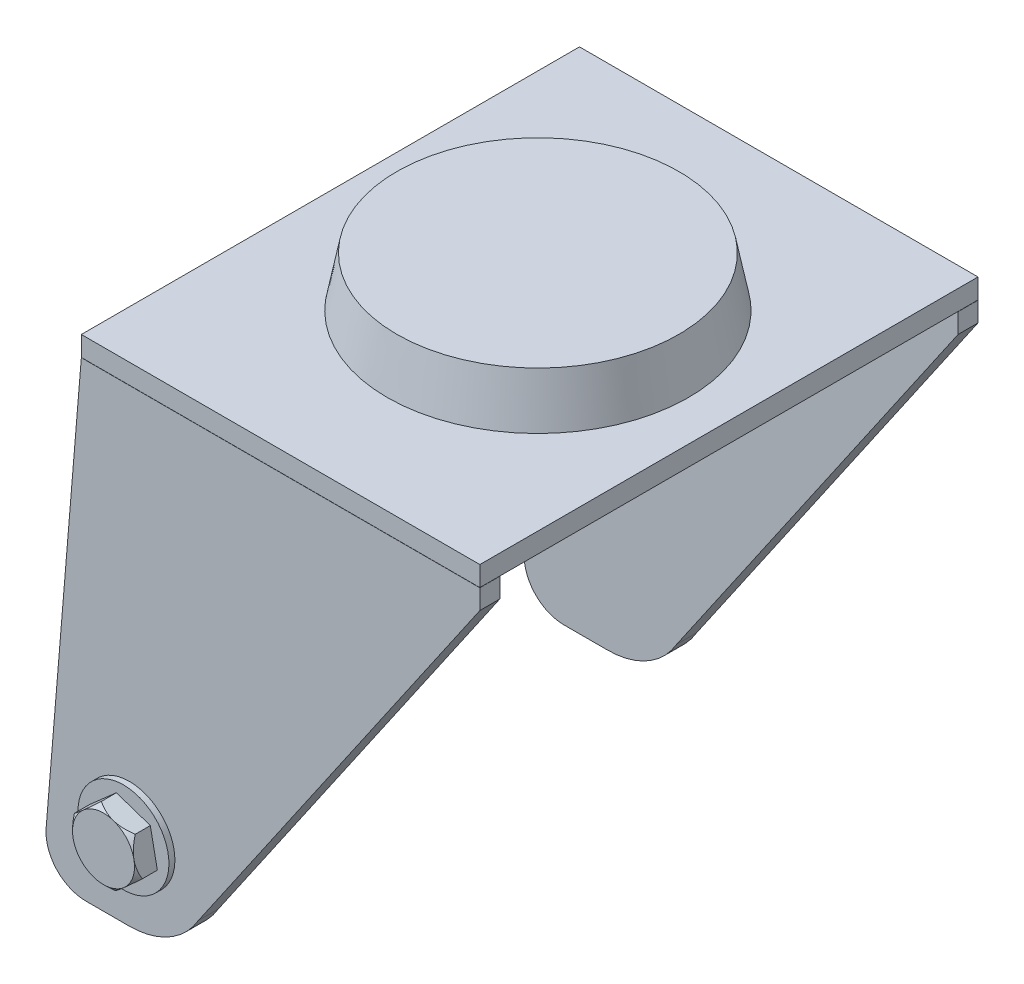
SolidWorks part; units mm, degrees
ref_plane "Front Plane" through (0, 0, 0) normal (0, 0, 1) x (1, 0, 0)
ref_plane "Top Plane" through (0, 0, 0) normal (0, 1, 0) x (1, 0, 0)
ref_plane "Right Plane" through (0, 0, 0) normal (1, 0, 0) x (0, 0, -1)
sketch "Sketch1" plane through (0, 0, 0) normal (0, 0, 1) x (1, 0, 0)
  line L0 (-24.1267, 195) -> (-41.8107, -18.4906)
  line L2 (0, -40.1416) -> (-21.879, -40.1416)
  line L4 (175.8733, 185) -> (175.8733, 195)
  line L6 (175.8733, 195) -> (-24.1267, 195)
  line L7 (107.781, 195) -> (175.8733, 195)
  line L9 (175.8733, 185) -> (34.5822, -20.3818)
  arc A0 (0, -40.1416) -> (34.5822, -20.3818) centre (0, 0) ccw
  arc A3 (-41.8107, -18.4906) -> (-21.879, -40.1416) centre (-21.879, -20.1416) ccw
  point P11 (0, 240)
  point P13 (0, 230)
  point P14 (-61.2112, 240)
  point P15 (-61.2112, 230)
  point P18 (-61.2112, 195)
  point P22 (259.8584, 185)
  point P23 (-24.1267, 185)
  dimension "D1" = 20
extrude "Boss-Extrude1" add sketch "Sketch1" along normal blind 10 contours L0 A3 L2 A0 L9 L4 L6
sketch "Sketch2" plane through (0, 0, -230) normal (0, 0, -1) x (-1, 0, 0)
  line L6 (41.8107, -18.4906) -> (24.1267, 195)
  line L7 (0, -40.1416) -> (21.879, -40.1416)
  line L8 (-175.8733, 185) -> (-34.5822, -20.3818)
  line L9 (-175.8733, 195) -> (-175.8733, 185)
  line L10 (24.1267, 195) -> (-175.8733, 195)
  line L11 (41.8107, -18.4906) -> (24.1267, 195)
  line L12 (0, -40.1416) -> (21.879, -40.1416)
  line L13 (-175.8733, 185) -> (-34.5822, -20.3818)
  line L14 (-175.8733, 195) -> (-175.8733, 185)
  line L15 (24.1267, 195) -> (-175.8733, 195)
  arc A2 (21.879, -40.1416) -> (41.8107, -18.4906) centre (21.879, -20.1416) ccw
  arc A3 (-34.5822, -20.3818) -> (0, -40.1416) centre (0, 0) ccw
  arc A4 (21.879, -40.1416) -> (41.8107, -18.4906) centre (21.879, -20.1416) ccw
  arc A5 (-34.5822, -20.3818) -> (0, -40.1416) centre (0, 0) ccw
  dimension "D1" = 0
extrude "Boss-Extrude2" add sketch "Sketch2" along normal blind 10 separate body
sketch "Sketch3" plane through (0, 195, 0) normal (0, 1, 0) x (1, 0, 0)
  line L2 (157.4304, -4.0507) -> (157.4304, -4.0629)
  line L3 (157.4304, -4.0629) -> (151.0495, -4.0629)
  line L4 (151.0495, -4.0507) -> (151.0495, -4.0629)
  line L5 (-24.1267, -10) -> (175.8733, -10)
  line L6 (-24.1267, -10) -> (-24.1267, 240)
  line L7 (-24.1267, 240) -> (175.8733, 240)
  line L8 (175.8733, -10) -> (175.8733, 240)
extrude "Boss-Extrude3" add sketch "Sketch3" along normal blind 10 separate body
sketch "Sketch4" plane through (0, 205, 0) normal (0, 1, 0) x (1, 0, 0)
  circle A0 centre (80, 115) radius 75.6517
extrude "Boss-Extrude4" add sketch "Sketch4" along normal blind 25 draft 11
sketch "Sketch5" plane through (0, 0, -240) normal (0, 0, -1) x (-1, 0, 0)
  circle A0 centre (0, 0) radius 22.8213
extrude "Boss-Extrude5" add sketch "Sketch5" along normal blind 3 separate body
sketch "Sketch6" plane through (0, 0, -243) normal (0, 0, -1) x (-1, 0, 0)
  line L1 (17.0231, 5.7473) -> (3.5343, 17.6161)
  line L2 (3.5343, 17.6161) -> (-13.4889, 11.8688)
  line L3 (-13.4889, 11.8688) -> (-17.0231, -5.7473)
  line L4 (-17.0231, -5.7473) -> (-3.5343, -17.6161)
  line L5 (-3.5343, -17.6161) -> (13.4889, -11.8688)
  line L6 (13.4889, -11.8688) -> (17.0231, 5.7473)
  circle A0 centre (0, 0) radius 15.56 construction
extrude "Boss-Extrude6" add sketch "Sketch6" along normal blind 10
sketch "Sketch7" plane through (0, 0, -253) normal (0, 0, -1) x (-1, 0, 0)
  circle A0 centre (0, 0) radius 15.56
  circle A1 centre (0, 0) radius 20.6216
sketch "Sketch8" plane through (0, 230, 0) normal (0, 1, 0) x (1, 0, 0)
  line L0 (9.2078, 115) -> (150.7922, 115)
  circle A0 centre (80, 115) radius 70.7922 construction
ref_plane "Plane1" through (0, 0, -115) normal (0, 0, 1) x (1, 0, 0)
extrude "Cut-Extrude2" cut sketch "Sketch7" against normal blind 10 draft 45
mirror "Mirror3" about plane through (0, 0, -115) normal (0, 0, 1) of bodies 105 110
sketch "Sketch9" plane through (0, 0, -240) normal (0, 0, -1) x (-1, 0, 0)
  line L1 (-175.8733, 195) -> (66.3945, 195)
  line L2 (-175.8733, 195) -> (-175.8733, 194.9)
  line L3 (-175.8733, 194.9) -> (66.3945, 194.9)
  line L4 (66.3945, 195) -> (66.3945, 194.9)
  dimension "D1" = 0.1
extrude "Cut-Extrude3" cut sketch "Sketch9" against normal blind 408
sketch "Sketch10" plane through (0, 0, -240) normal (0, 0, -1) x (-1, 0, 0)
  text T0 "<b>BLICKLE LSD-GTH 304K (HR)</b>" font "Century Gothic" height 10
extrude "Cut-Extrude4" cut sketch "Sketch10" against normal blind 0.1
